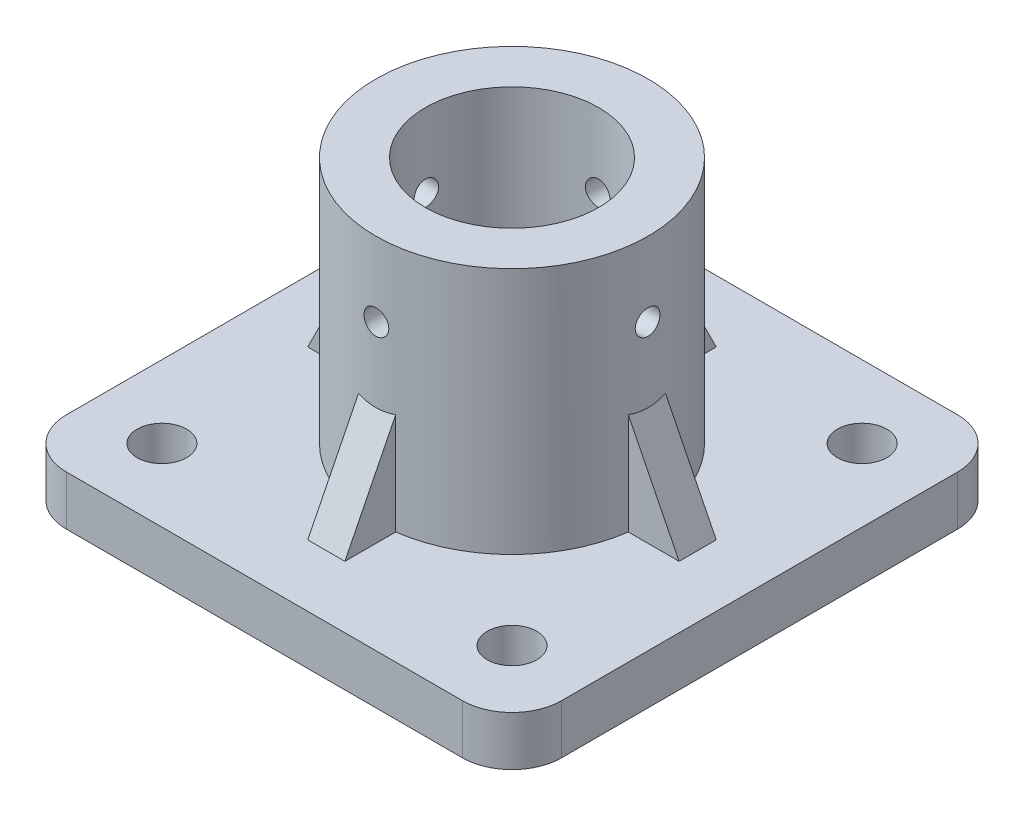
SolidWorks part; units mm, degrees
ref_plane "Front Plane" through (0, 0, 0) normal (0, 0, 1) x (1, 0, 0)
ref_plane "Top Plane" through (0, 0, 0) normal (0, 1, 0) x (1, 0, 0)
ref_plane "Right Plane" through (0, 0, 0) normal (1, 0, 0) x (0, 0, -1)
sketch "Sketch2" plane through (0, 0, 0) normal (0, 1, 0) x (1, 0, 0)
  line L1 (-80, -100) -> (80, -100)
  line L2 (-100, -80) -> (-100, 80)
  line L3 (-80, 100) -> (80, 100)
  line L4 (100, -80) -> (100, 80)
  line L5 (-100, -100) -> (100, 100) construction
  line L6 (-100, 100) -> (100, -100) construction
  circle A0 centre (-70.7107, 70.7107) radius 10
  circle A1 centre (70.7107, 70.7107) radius 10
  circle A2 centre (-70.7107, -70.7107) radius 10
  circle A3 centre (70.7107, -70.7107) radius 10
  arc A4 (80, 100) -> (100, 80) centre (80, 80) cw
  arc A5 (80, -100) -> (100, -80) centre (80, -80) ccw
  arc A6 (-80, -100) -> (-100, -80) centre (-80, -80) cw
  arc A7 (-100, 80) -> (-80, 100) centre (-80, 80) cw
  circle A8 centre (0, 0) radius 35
  point P0 (0, 0)
  point P14 (0, 0)
  dimension "D3" = 20
  dimension "D5" = 20
  dimension "D6" = 70
  dimension "D1" = 200
  dimension "D2" = 200
  dimension "D4" = 100
extrude "Boss-Extrude1" add sketch "Sketch2" along normal blind 20
sketch "Sketch5" plane through (0, 20, 0) normal (0, 1, 0) x (1, 0, 0)
  circle A0 centre (0, 0) radius 35
  circle A3 centre (0, 0) radius 55
  circle A4 centre (0, 0) radius 35 construction
  dimension "D1" = 20
extrude "Boss-Extrude2" add sketch "Sketch5" along normal blind 100
sketch "Sketch6" plane through (0, 0, 0) normal (0, 0, 1) x (1, 0, 0)
  line L0 (55, 60) -> (75, 20)
  line L1 (55, 20) -> (55, 120) construction
  line L2 (-80, 20) -> (80, 20) construction
  dimension "D1" = 20
  dimension "D2" = 40
rib "Rib1" sketch "Sketch6" sketch "Sketch6" thickness 15 extrusion direction parallel to sketch draft on no parameters "D1"=15
pattern_circular "CirPattern1" count 4 over 360 about axis through (0, 0, 0) along (0, 1, 0) of "Rib1"
sketch "Sketch7" plane through (0, 0, 0) normal (0, 0, 1) x (1, 0, 0)
  line L0 (55, 120) -> (-55, 120) construction
  circle A0 centre (0, 90) radius 5
  point P4 (0, 0)
  dimension "D1" = 10
  dimension "D2" = 30
extrude "Cut-Extrude2" cut sketch "Sketch7" against normal through all contours A0
pattern_circular "CirPattern2" count 4 over 360 of "Cut-Extrude2"
